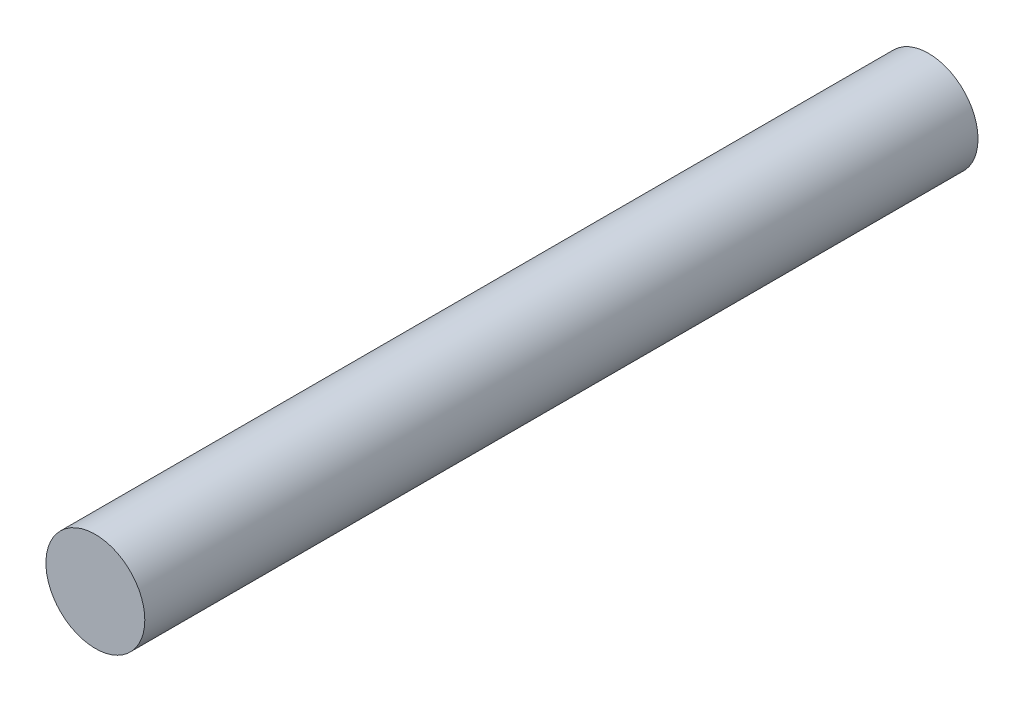
SolidWorks part; units mm, degrees
ref_plane "Front Plane" through (0, 0, 0) normal (0, 0, 1) x (1, 0, 0)
ref_plane "Top Plane" through (0, 0, 0) normal (0, 1, 0) x (1, 0, 0)
ref_plane "Right Plane" through (0, 0, 0) normal (1, 0, 0) x (0, 0, -1)
sketch "Sketch2" plane through (0, 0, 0) normal (0, 0, 1) x (1, 0, 0)
  circle A0 centre (0, 0) radius 2
extrude "Boss-Extrude1" add sketch "Sketch2" along normal blind 33.7
